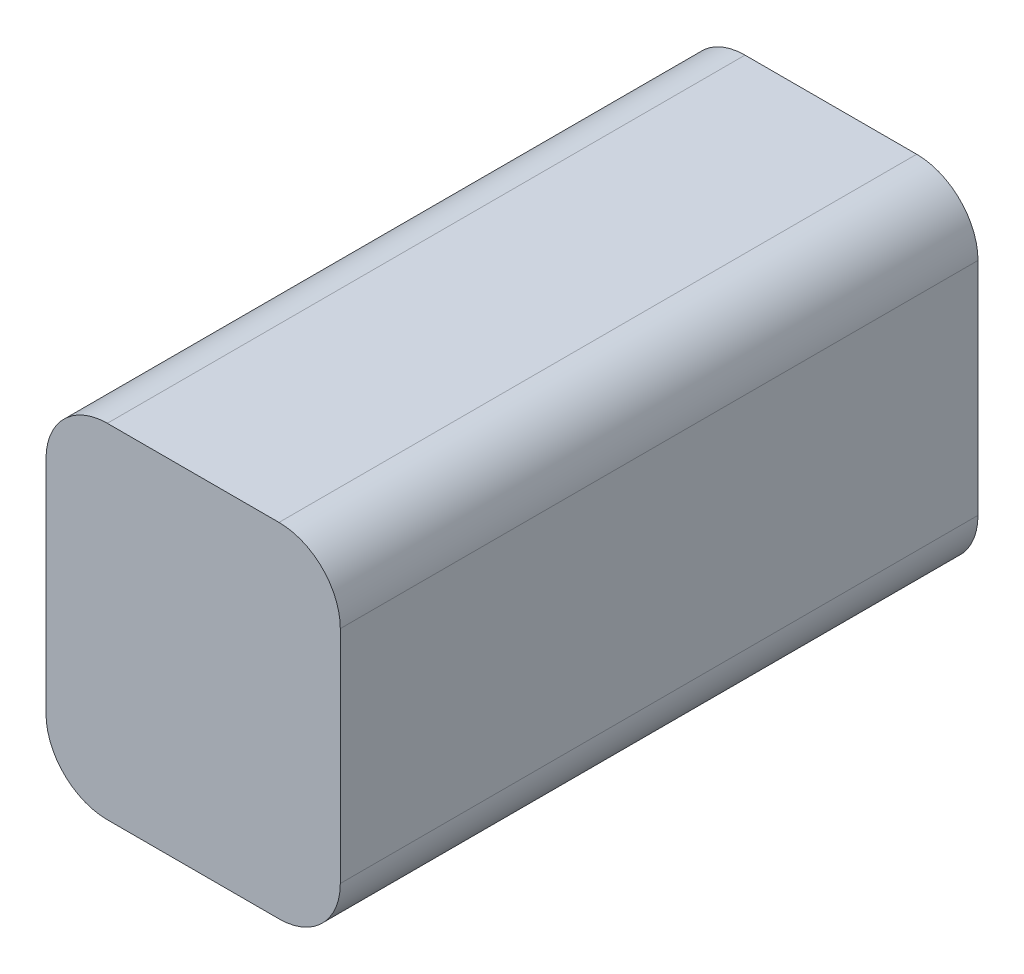
SolidWorks part; units mm, degrees
ref_plane "Front" through (0, 0, 0) normal (0, 0, 1) x (1, 0, 0)
ref_plane "Top" through (0, 0, 0) normal (0, 1, 0) x (1, 0, 0)
ref_plane "Right" through (0, 0, 0) normal (1, 0, 0) x (0, 0, -1)
sketch "Sketch1" plane through (0, 0, 0) normal (0, 1, 0) x (1, 0, 0)
  line L1 (-12, -26) -> (12, -26)
  line L2 (-12, -26) -> (-12, 26)
  line L3 (-12, 26) -> (12, 26)
  line L4 (12, -26) -> (12, 26)
  line L5 (-12, -26) -> (12, 26) construction
  line L6 (-12, 26) -> (12, -26) construction
  point P0 (0, 0)
  dimension "D1" = 52
  dimension "D2" = 24
extrude "Boss-Extrude1" add sketch "Sketch1" along normal blind 28
fillet "Fillet1" radius 5 4 edges at (-12, 0, 0) (12, 0, 0) (-12, 28, 0) (12, 28, 0)
